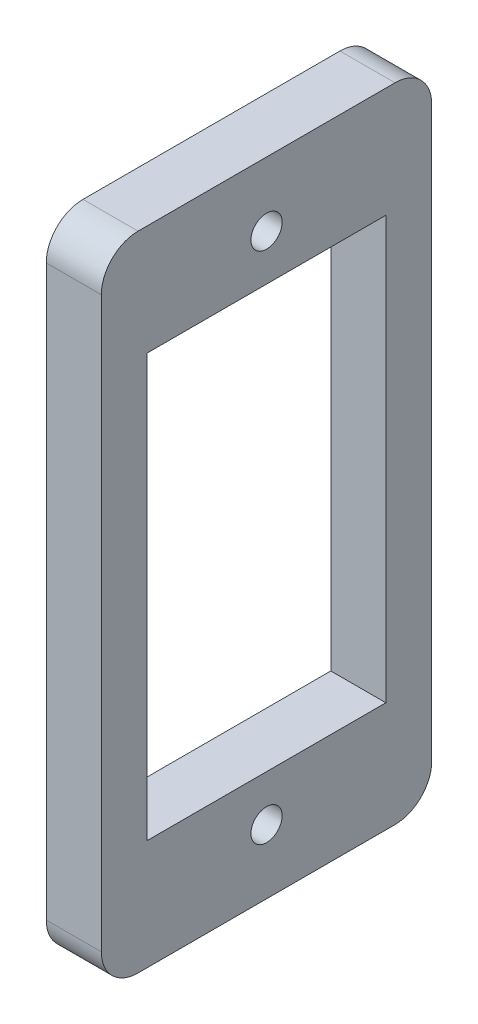
SolidWorks part; units mm, degrees
ref_plane "Plano frontal" through (0, 0, 0) normal (0, 0, 1) x (1, 0, 0)
ref_plane "Plano superior" through (0, 0, 0) normal (0, 1, 0) x (1, 0, 0)
ref_plane "Plano direito" through (0, 0, 0) normal (1, 0, 0) x (0, 0, -1)
sketch "Esboço1" plane through (0, 0, 0) normal (1, 0, 0) x (0, 0, -1)
  line L1 (-9, -17.5) -> (9, -17.5)
  line L2 (-9, -17.5) -> (-9, 17.5)
  line L3 (-9, 17.5) -> (9, 17.5)
  line L4 (9, -17.5) -> (9, 17.5)
  line L5 (-9, -17.5) -> (9, 17.5) construction
  line L6 (-9, 17.5) -> (9, -17.5) construction
  point P0 (0, 0)
  point P5 (0, 0)
  dimension "D1" = 35
  dimension "D2" = 18
extrude "Ressalto-extrusão1" add sketch "Esboço1" along normal blind 3
sketch "Esboço2" plane through (3, 0, 0) normal (1, 0, 0) x (0, 0, -1)
  line L1 (6.5, -11.5) -> (-6.5, -11.5)
  line L2 (6.5, -11.5) -> (6.5, 11.5)
  line L3 (6.5, 11.5) -> (-6.5, 11.5)
  line L4 (-6.5, -11.5) -> (-6.5, 11.5)
  line L5 (6.5, -11.5) -> (-6.5, 11.5) construction
  line L6 (6.5, 11.5) -> (-6.5, -11.5) construction
  point P0 (0, 0)
  dimension "D1" = 13
  dimension "D2" = 23
extrude "Corte-extrusão1" cut sketch "Esboço2" against normal up to next
sketch "Esboço3" plane through (0, 0, 0) normal (-1, 0, 0) x (0, 0, 1)
  line L0 (-12.3301, 0) -> (12.3301, 0) construction
  circle A0 centre (0, 14) radius 0.85
  circle A1 centre (0, -14) radius 0.85
  point P7 (0, 0)
  point P8 (0, 0)
  dimension "D1" = 1.7
  dimension "D2" = 14
extrude "Corte-extrusão2" cut sketch "Esboço3" against normal up to next
fillet "Filete1" radius 2 4 edges at (1.5, -17.5, 9) (1.5, -17.5, -9) (1.5, 17.5, 9) (1.5, 17.5, -9)
